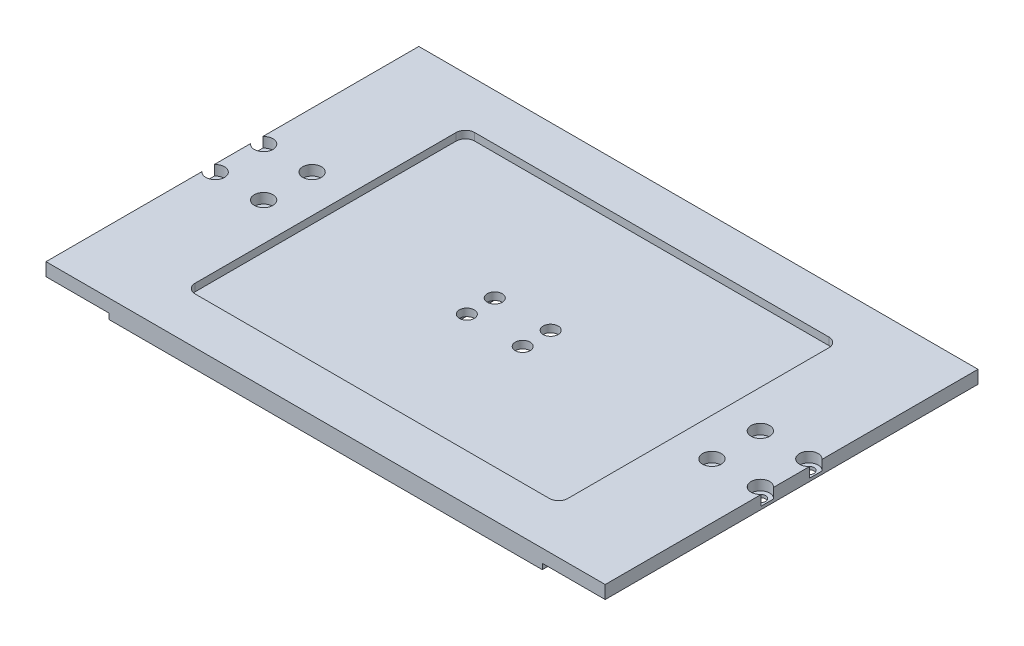
SolidWorks part; units mm, degrees
material "3.3535 (EN-AW 5754)"
ref_plane "Front Plane" through (0, 0, 0) normal (0, 0, 1) x (1, 0, 0)
ref_plane "Top Plane" through (0, 0, 0) normal (0, 1, 0) x (1, 0, 0)
ref_plane "Right Plane" through (0, 0, 0) normal (1, 0, 0) x (0, 0, -1)
sketch "Sketch1" plane through (0, 0, 0) normal (0, 1, 0) x (1, 0, 0)
  line L1 (150, -100) -> (-150, -100)
  line L2 (150, -100) -> (150, 100)
  line L3 (150, 100) -> (-150, 100)
  line L4 (-150, -100) -> (-150, 100)
  line L5 (150, -100) -> (-150, 100) construction
  line L6 (150, 100) -> (-150, -100) construction
  point P0 (0, 0)
  dimension "D1" = 300
  dimension "D2" = 200
extrude "Boss-Extrude1" add sketch "Sketch1" along normal blind 10 contours L3 L4 L1 L2
sketch "Sketch2" plane through (0, 0, 100) normal (0, 0, 1) x (1, 0, 0)
  line L1 (-150, 0) -> (-116.25, 0)
  line L2 (-150, 0) -> (-150, 3)
  line L3 (-150, 3) -> (-116.25, 3)
  line L4 (-116.25, 0) -> (-116.25, 3)
  line L5 (150, 0) -> (116.25, 0)
  line L6 (150, 0) -> (150, 3)
  line L7 (150, 3) -> (116.25, 3)
  line L8 (116.25, 0) -> (116.25, 3)
  dimension "D1" = 33.75
  dimension "D2" = 3
  dimension "D3" = 3
  dimension "D4" = 33.75
extrude "Cut-Extrude1" cut sketch "Sketch2" against normal through all both and the other way through all
sketch "Sketch3" plane through (0, 10, 0) normal (0, 1, 0) x (1, 0, 0)
  line L1 (100, -75) -> (-100, -75)
  line L2 (100, -75) -> (100, 75)
  line L3 (100, 75) -> (-100, 75)
  line L4 (-100, -75) -> (-100, 75)
  line L5 (100, -75) -> (-100, 75) construction
  line L6 (100, 75) -> (-100, -75) construction
  point P0 (0, 0)
  dimension "D1" = 200
  dimension "D2" = 150
extrude "Cut-Extrude2" cut sketch "Sketch3" against normal blind 4
fillet "Fillet1" radius 5 4 edges at (-100, 8, 75) (100, 8, 75) (100, 8, -75) (-100, 8, -75)
hole_wizard "CBORE for M5 Hex Socket Head Cap Screw1" positions "Sketch4" profile "Sketch5" counterbore size "M5" standard "ISO" end condition through all
sketch "Sketch4" plane through (0, 10, 0) normal (0, 1, 0) x (1, 0, 0)
  point P0 (146.25, 13)
  point P3 (120.25, 13)
  point P6 (120.25, -13)
  point P9 (146.25, -13)
  point P13 (-146.25, 13)
  point P16 (-120.25, 13)
  point P19 (-146.25, -13)
  point P22 (-120.25, -13)
  point P27 (0, 0)
  point P28 (0, 0)
  point P29 (0, 0)
  point P30 (0, 0)
  point P31 (0, 0)
  point P32 (0, 0)
  point P33 (0, 0)
  point P34 (0, 0)
sketch "Sketch5" plane through (146.25, 10, -13) normal (1, 0, 0) x (0, 0, 1)
  line L0 (0, 0) -> (0, 10)
  line L1 (0, 10) -> (2.75, 10)
  line L3 (2.75, 10) -> (2.75, 5.4)
  line L4 (2.75, 5.4) -> (5, 5.4)
  line L5 (5, 5.4) -> (5, 0)
  line L7 (5, 0) -> (0, 0)
  line L11 (0, -6.35) -> (0, 107.95) construction
  dimension "Thru Hole Dia." = 5.5
  dimension "Thru Hole Depth" = 10
  dimension "C'Bore Dia." = 10
  dimension "C'Bore Depth" = 5.4
sketch "Sketch6" plane through (0, 0, 0) normal (0, -1, 0) x (1, 0, 0)
  line L1 (18.25, -15) -> (-21.75, -15)
  line L2 (18.25, -15) -> (18.25, 15)
  line L3 (18.25, 15) -> (-21.75, 15)
  line L4 (-21.75, -15) -> (-21.75, 15)
  line L5 (18.25, -15) -> (-21.75, 15) construction
  line L6 (18.25, 15) -> (-21.75, -15) construction
  point P0 (0, 0)
  point P6 (0, 0)
  point P7 (0, 0)
  dimension "D1" = 40
  dimension "D2" = 30
extrude "Cut-Extrude3" cut sketch "Sketch6" against normal blind 2
hole_wizard "CBORE for M4 Hex Socket Head Cap Screw1" positions "Sketch7" profile "Sketch8" counterbore size "M4" standard "ISO"
sketch "Sketch7" plane through (0, 6, 0) normal (0, 1, 0) x (1, 0, 0)
  point P0 (13.25, 7.5)
  point P3 (13.25, -7.5)
  point P6 (-16.75, 7.5)
  point P9 (-16.75, -7.5)
sketch "Sketch8" plane through (13.25, 6, -7.5) normal (1, 0, 0) x (0, 0, 1)
  line L0 (0, 0) -> (0, 12.8519)
  line L1 (0, 12.8519) -> (2.25, 11.5)
  line L2 (2.25, 11.5) -> (2.25, 4.4)
  line L3 (2.25, 4.4) -> (4, 4.4)
  line L4 (4, 4.4) -> (4, 0)
  line L5 (4, 0) -> (0, 0)
  line L10 (0, 12.8519) -> (-2.25, 11.5) construction
  line L11 (0, -6.35) -> (0, 107.95) construction
  dimension "Hole Dia." = 4.5
  dimension "Hole Depth" = 11.5
  dimension "C'Bore Dia." = 8
  dimension "C'Bore Depth" = 4.4
  dimension "Drill Angle" = 118
